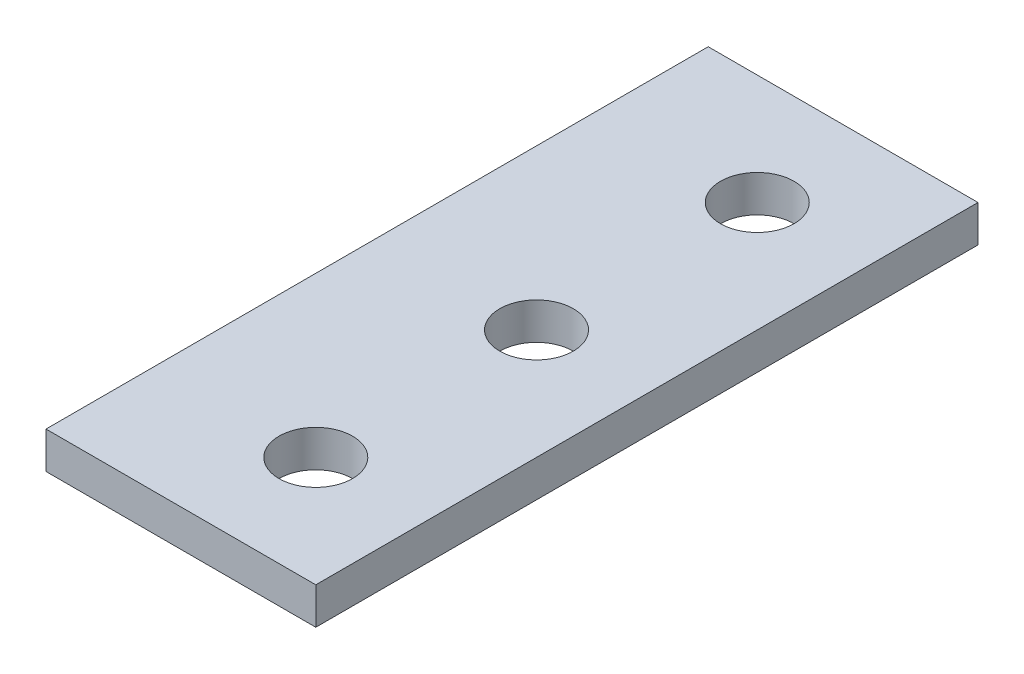
SolidWorks part; units mm, degrees
ref_plane "Front Plane" through (0, 0, 0) normal (0, 0, 1) x (1, 0, 0)
ref_plane "Top Plane" through (0, 0, 0) normal (0, 1, 0) x (1, 0, 0)
ref_plane "Right Plane" through (0, 0, 0) normal (1, 0, 0) x (0, 0, -1)
sketch "Sketch1" plane through (0, 0, 0) normal (0, 1, 0) x (1, 0, 0)
  line L1 (0, 0) -> (66, 0)
  line L2 (0, 0) -> (0, -162)
  line L3 (0, -162) -> (66, -162)
  line L4 (66, 0) -> (66, -162)
  circle A0 centre (39, -135) radius 9
  circle A1 centre (39, -81) radius 9
  circle A2 centre (39, -27) radius 9
  point P11 (0, 0)
  point P12 (0, 0)
  point P13 (0, 0)
  point P16 (33.3977, -27.3644)
  dimension "D3" = 18
  dimension "D1" = 66
  dimension "D2" = 162
  dimension "D4" = 54
  dimension "D5" = 54
  dimension "D6" = 27
  dimension "D7" = 27
extrude "Boss-Extrude2" add sketch "Sketch1" along normal mid plane 9
